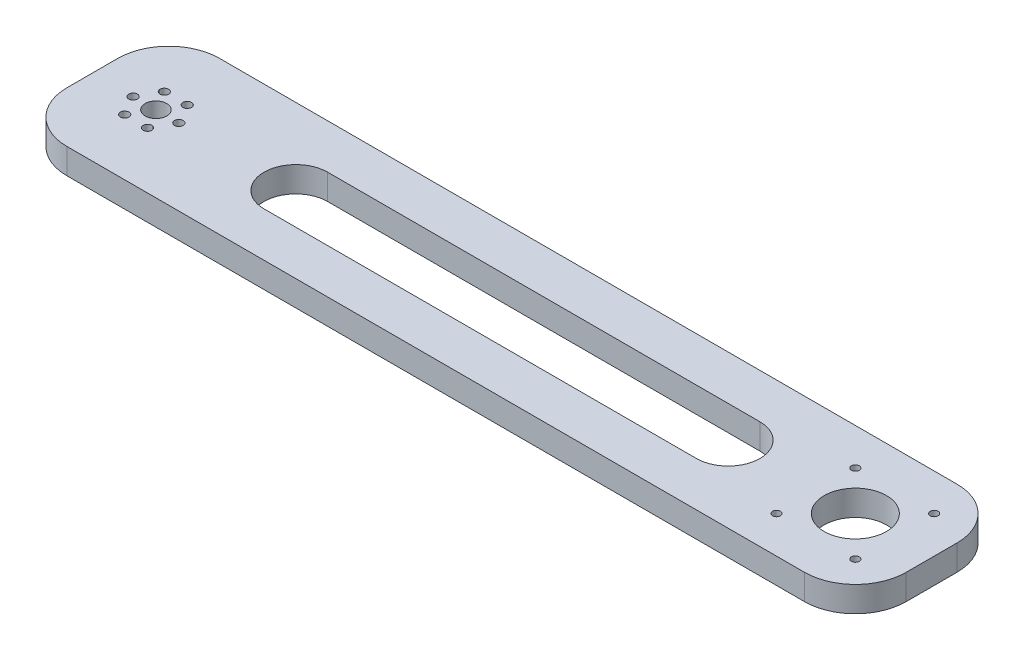
SolidWorks part; units mm, degrees
ref_plane "前视基准面" through (0, 0, 0) normal (0, 0, 1) x (1, 0, 0)
ref_plane "上视基准面" through (0, 0, 0) normal (0, 1, 0) x (1, 0, 0)
ref_plane "右视基准面" through (0, 0, 0) normal (1, 0, 0) x (0, 0, -1)
other "Configuration Table"
sketch "草图1" plane through (0, 0, 0) normal (0, 1, 0) x (1, 0, 0)
  line L1 (-165, -30) -> (165, -30)
  line L2 (-165, -30) -> (-165, 30)
  line L3 (-165, 30) -> (165, 30)
  line L4 (165, -30) -> (165, 30)
  line L5 (-165, -30) -> (165, 30) construction
  line L6 (-165, 30) -> (165, -30) construction
  point P0 (0, 0)
  dimension "D1" = 330
  dimension "D2" = 60
extrude "凸台-拉伸1" add sketch "草图1" along normal blind 10
fillet "圆角1" radius 20 4 edges at (165, 5, 30) (165, 5, -30) (-165, 5, -30) (-165, 5, 30)
sketch "草图5" plane through (0, 10, 0) normal (0, 1, 0) x (1, 0, 0)
  line L0 (165, 0) -> (-165, 0) construction
  line L1 (165, -10) -> (165, 10) construction
  line L2 (-165, 10) -> (-165, -10) construction
  circle A0 centre (135, 0) radius 12.25
  dimension "D1" = 24.5
  dimension "D2" = 30
extrude "切除-拉伸3" cut sketch "草图5" against normal blind 12
sketch "草图9" plane through (0, 0, 0) normal (0, -1, 0) x (1, 0, 0)
  circle A0 centre (119.5, 15.5) radius 1.55
  circle A1 centre (150.5, 15.5) radius 1.55
  circle A2 centre (150.5, -15.5) radius 1.55
  circle A3 centre (119.5, -15.5) radius 1.55
  dimension "D1" = 3.1
  dimension "D2" = 3.1
  dimension "D3" = 3.1
  dimension "D4" = 3.1
extrude "切除-拉伸6" cut sketch "草图9" against normal through all
sketch "草图11" plane through (0, 0, 0) normal (0, -1, 0) x (1, 0, 0)
  line L0 (-145, 30) -> (145, 30) construction
  line L1 (-165, -10) -> (-165, 10) construction
  circle A0 centre (-140, 0) radius 4.25
  dimension "D1" = 8.5
  dimension "D2" = 30
  dimension "D3" = 25
extrude "切除-拉伸8" cut sketch "草图11" against normal through all
sketch "草图15" plane through (0, 0, 0) normal (0, -1, 0) x (1, 0, 0)
  line L0 (-85, 0) -> (85, 0) construction
  line L1 (-85, 12.5) -> (85, 12.5)
  line L2 (-85, -12.5) -> (85, -12.5)
  arc A0 (-85, 12.5) -> (-85, -12.5) centre (-85, 0) ccw
  arc A1 (85, -12.5) -> (85, 12.5) centre (85, 0) ccw
  point P2 (0, 0)
  dimension "D1" = 170
  dimension "D2" = 25
extrude "切除-拉伸11" cut sketch "草图15" against normal through all
sketch "草图16" plane through (0, 0, 0) normal (0, -1, 0) x (1, 0, 0)
  circle A0 centre (-140, 0) radius 9 construction
  circle A1 centre (-149, 0) radius 1.7
  dimension "D1" = 18
  dimension "D2" = 3.4
extrude "切除-拉伸12" cut sketch "草图16" against normal through all
cosmetic thread "装饰螺纹线3" parameters "D1"=10, "D2"=4.4
pattern_circular "阵列(圆周)1" count 6 every 60 about axis through (-140, 0, 0) along (0, 1, 0) of "切除-拉伸12"
cosmetic thread "装饰螺纹线4" parameters "D1"=10, "D2"=4.4
